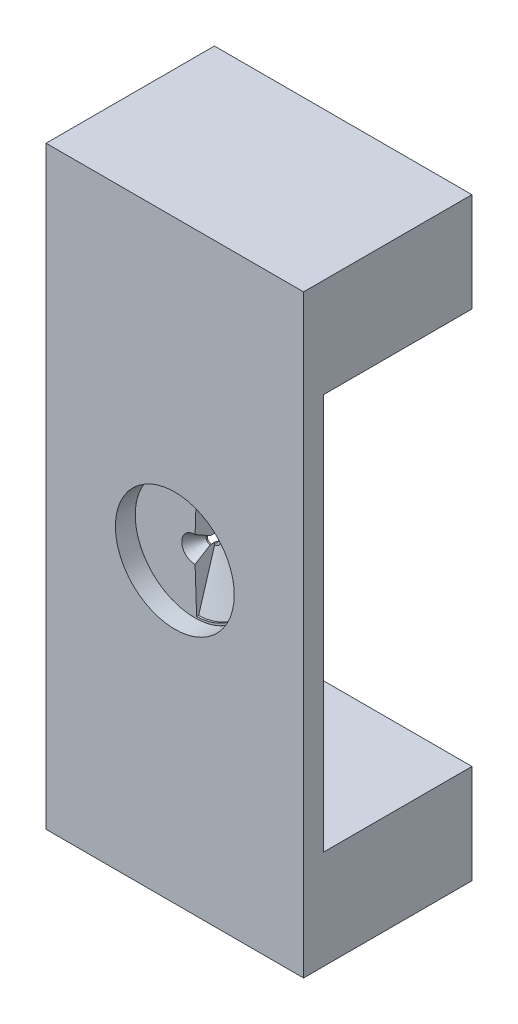
SolidWorks part; units mm, degrees
ref_plane "前视基准面" through (0, 0, 0) normal (0, 0, 1) x (1, 0, 0)
ref_plane "上视基准面" through (0, 0, 0) normal (0, 1, 0) x (1, 0, 0)
ref_plane "右视基准面" through (0, 0, 0) normal (1, 0, 0) x (0, 0, -1)
sketch "草图1" plane through (0, 0, 0) normal (0, 0, 1) x (1, 0, 0)
  line L1 (30, -13) -> (-30, -13)
  line L2 (30, -13) -> (30, 13)
  line L3 (30, 13) -> (-30, 13)
  line L4 (-30, -13) -> (-30, 13)
  line L5 (30, -13) -> (-30, 13) construction
  line L6 (30, 13) -> (-30, -13) construction
  circle A0 centre (0, 0) radius 6
  point P0 (0, 0)
  dimension "D3" = 12
  dimension "D1" = 26
  dimension "D2" = 60
extrude "凸台-拉伸1" add sketch "草图1" along normal blind 2
sketch "草图2" plane through (0, 0, 0) normal (0, 0, -1) x (-1, 0, 0)
  line L0 (30, 13) -> (30, -13)
  line L1 (30, -13) -> (20, -13)
  line L2 (30, -13) -> (-30, -13) construction
  line L3 (20, -13) -> (20, 13)
  line L4 (-30, 13) -> (30, 13) construction
  line L5 (20, 13) -> (30, 13)
  line L6 (0, 0) -> (0, -13) construction
  line L7 (-20, -13) -> (-20, 13)
  line L8 (-30, -13) -> (-20, -13)
  line L9 (-30, 13) -> (-30, -13)
  line L10 (-20, 13) -> (-30, 13)
  dimension "D1" = 10
sketch "草图3" plane through (0, 0, 0) normal (0, 0, -1) x (-1, 0, 0)
  circle A1 centre (0, 0) radius 6 construction
  circle A2 centre (0, 0) radius 6
extrude "凸台-拉伸3" add sketch "草图3" along normal blind 2.2 separate body
sketch "草图5" plane through (0, 0, 0) normal (0, 1, 0) x (1, 0, 0)
  line L5 (0, 0) -> (0, 5.0245) construction
  line L8 (-1.4, 0.2) -> (-1.4, 2.2)
  line L9 (6, 2.2) -> (-6, 2.2) construction
  line L10 (-1.4, 2.2) -> (-6, 2.2)
  line L11 (-6, 2.2) -> (-6, 0.2)
  line L13 (-6, 0.2) -> (-1.4, 0.2)
  dimension "D1" = 1.4
  dimension "D2" = 2
extrude "切除-拉伸1" cut sketch "草图5" against normal mid plane 12 contours L8 L10 L11 L13
sketch "草图6" plane through (0, 0, 0) normal (0, 1, 0) x (1, 0, 0)
  line L0 (0, 0) -> (0, 2.2) construction
  line L1 (6, 2.2) -> (-1.4, 2.2) construction
  line L3 (0, 0) -> (6, 0) construction
  line L5 (6, 0) -> (6, 2.2) construction
  line L6 (6, 0.2) -> (6, 2.2) construction
  line L8 (0.5, 2.2) -> (6, 2.2)
  line L9 (6, 2.2) -> (6, 0.2)
  line L12 (6, 0.2) -> (0.5, 2.2)
  dimension "D1" = 0.5
  dimension "D2" = 0.2
sketch "草图7" plane through (0, 0, -2.2) normal (0, 0, -1) x (-1, 0, 0)
  circle A0 centre (0, 0) radius 0.2
  dimension "D1" = 0.4
extrude "切除-拉伸2" cut sketch "草图7" against normal blind 12
revolve "切除-旋转4" cut sketch "草图6" angle 90 about L0 other way angle 90
sketch "草图9" plane through (0, 0, 0) normal (0, 1, 0) x (1, 0, 0)
  line L0 (-1.4, 0.2) -> (-6, 0.2) construction
  line L1 (-1.4, 0.2) -> (-6, 0.2)
  line L2 (-1.4, 0.2) -> (-0.4685, 1.7)
  line L3 (-0.4685, 1.7) -> (0, 1.7)
  line L4 (0, 2.2) -> (0, 0.2) construction
  line L5 (0, 1.7) -> (0, 0.2) construction
  line L6 (0, 0.2) -> (-1.4, 0.2)
  line L7 (-1.4, 2.2) -> (-6, 2.2)
  line L8 (-1.4, 2.2) -> (0, 2.2)
  line L9 (0, 2.2) -> (0, 1.7)
  line L10 (-6, 2.2) -> (-6, 0.2)
  dimension "D1" = 121.84
  dimension "D2" = 1.5
revolve "切除-旋转5" cut sketch "草图9" angle 90 about L5 other way angle 90
sketch "草图12" plane through (0, 0, 0) normal (0, 1, 0) x (1, 0, 0)
  line L0 (0.2, 0.2) -> (5.8, 0.2) construction
  line L1 (0, 0.2) -> (6, 0.2) construction
  line L2 (5.8, 0.2) -> (0.6222, 2)
  line L3 (0.6222, 2) -> (0.2, 2)
  line L4 (0.2, 2) -> (0.2, 0.2)
  line L5 (0.5, 2.2) -> (0, 2.2) construction
  line L6 (0, 2.2) -> (0, 3.4987) construction
  line L7 (0.2, 0.2) -> (0.2, -0.4349)
  line L8 (0.2, -0.4349) -> (5.8, -0.4349)
  line L9 (5.8, -0.4349) -> (5.8, 0.2)
  dimension "D1" = 0.2
  dimension "D2" = 0.2
  dimension "D3" = 5.6
  dimension "D4" = 1.8
revolve "切除-旋转6" cut sketch "草图12" angle 88 about L6 other way angle 88
sketch "草图13" plane through (0, 0, 0) normal (0, 0, 1) x (1, 0, 0)
  circle A0 centre (0, 0) radius 1.3
  dimension "D1" = 2.6
sketch "草图14" plane through (0, 0, -2) normal (0, 0, 1) x (1, 0, 0)
  circle A0 centre (0, 0) radius 0.4
  dimension "D1" = 0.8
sketch "草图16" plane through (0, 0, -2.2) normal (0, 0, -1) x (-1, 0, 0)
  circle A0 centre (0, 0) radius 0.4
  dimension "D1" = 0.8
sketch "草图17" plane through (0, 0, 0) normal (0, 0, 1) x (1, 0, 0)
  circle A0 centre (0, 0) radius 1.3
  dimension "D1" = 2.6
ref_plane "基准面1" through (0, 0, -1.7) normal (0, 0, -1) x (-1, 0, 0)
ref_plane "基准面2" through (0, 0, -1.5) normal (0, 0, -1) x (-1, 0, 0)
sketch "草图18" plane through (0, 0, -1.5) normal (0, 0, -1) x (-1, 0, 0)
  circle A0 centre (0, 0) radius 0.4
  dimension "D1" = 0.8
sketch "草图19" plane through (0, 0, 0) normal (0, 1, 0) x (1, 0, 0)
  line L3 (-0.4, 1.5688) -> (0, 1.5688)
  line L4 (0, 0.2) -> (0, 1.7) construction
  line L11 (0, 0) -> (0, -0.3879) construction
  line L12 (-0.4, 1.5688) -> (-1.3, 0)
  line L16 (30, 0) -> (-30, 0) construction
  line L17 (-1.3, 0) -> (0, 0)
  line L18 (0, 0) -> (0, 1.5688)
  dimension "D1" = 0.4
  dimension "D2" = 1.3
extrude "切除-拉伸4" cut sketch "草图16" against normal blind 0.7
revolve "切除-旋转8" cut sketch "草图19" angle 360 about L11
sketch "草图20" plane through (0, 0, 2) normal (0, 0, 1) x (1, 0, 0)
  line L0 (30, 13) -> (-30, 13) construction
  line L1 (-13, -13) -> (13, -13)
  line L2 (-13, -13) -> (-13, 13) construction
  line L3 (-13, 13) -> (13, 13)
  line L4 (13, -13) -> (13, 13) construction
  line L5 (-13, -13) -> (13, 13) construction
  line L6 (-13, 13) -> (13, -13) construction
  line L7 (-30, 13) -> (-30, -13)
  line L8 (-30, -13) -> (-13, -13)
  line L9 (-13, -13) -> (-13, 13)
  line L10 (-13, 13) -> (-30, 13)
  line L11 (13, -13) -> (30, -13)
  line L12 (30, -13) -> (30, 13)
  line L13 (30, 13) -> (13, 13)
  line L14 (13, 13) -> (13, -13)
  point P0 (0, 0)
extrude "切除-拉伸5" cut sketch "草图20" against normal blind 10
sketch "草图21" plane through (0, 13, 0) normal (0, 1, 0) x (1, 0, 0)
  line L4 (13, 0) -> (-13, 0)
  line L5 (-13, 0) -> (-13, -2)
  line L6 (-13, -2) -> (13, -2)
  line L7 (13, -2) -> (13, 0)
  line L8 (13, 0) -> (-13, 0)
  line L9 (-13, 0) -> (-13, -2)
  line L10 (-13, -2) -> (13, -2)
  line L11 (13, -2) -> (13, 0)
  dimension "D1" = 0
extrude "凸台-拉伸4" add sketch "草图21" along normal blind 17
sketch "草图22" plane through (0, -13, 0) normal (0, -1, 0) x (1, 0, 0)
  line L4 (13, 2) -> (-13, 2)
  line L5 (-13, 2) -> (-13, 0)
  line L6 (-13, 0) -> (13, 0)
  line L7 (13, 0) -> (13, 2)
  line L8 (13, 2) -> (-13, 2)
  line L9 (-13, 2) -> (-13, 0)
  line L10 (-13, 0) -> (13, 0)
  line L11 (13, 0) -> (13, 2)
  dimension "D1" = 0
extrude "凸台-拉伸6" add sketch "草图22" along normal blind 17
sketch "草图23" plane through (0, 0, 0) normal (0, 0, -1) x (-1, 0, 0)
  line L1 (-13, 30) -> (13, 30) construction
  line L2 (0, 0) -> (6, 0) construction
  line L3 (-13, 30) -> (13, 30)
  line L4 (13, 30) -> (13, 20)
  line L5 (13, -30) -> (13, 30) construction
  line L6 (13, 20) -> (-13, 20)
  line L7 (-13, 30) -> (-13, -30) construction
  line L8 (-13, 20) -> (-13, 30)
  line L9 (13, -20) -> (-13, -20)
  line L10 (13, -30) -> (13, -20)
  line L11 (-13, -30) -> (13, -30)
  line L12 (-13, -20) -> (-13, -30)
  circle A0 centre (0, 0) radius 6 construction
  dimension "D1" = 10
extrude "凸台-拉伸7" add sketch "草图23" along normal blind 15
